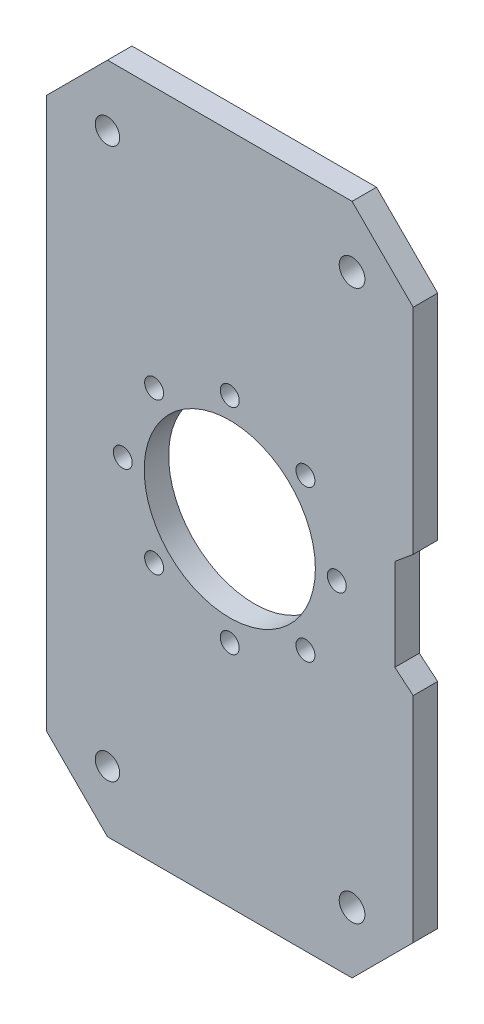
SolidWorks part; units mm, degrees
ref_plane "前视基准面" through (0, 0, 0) normal (0, 0, 1) x (1, 0, 0)
ref_plane "上视基准面" through (0, 0, 0) normal (0, 1, 0) x (1, 0, 0)
ref_plane "右视基准面" through (0, 0, 0) normal (1, 0, 0) x (0, 0, -1)
sketch "草图1" plane through (0, 0, 0) normal (0, 0, 1) x (1, 0, 0)
  line L1 (30, -55) -> (-30, -55)
  line L2 (30, -55) -> (30, 55)
  line L3 (30, 55) -> (-30, 55)
  line L4 (-30, -55) -> (-30, 55)
  line L5 (30, -55) -> (-30, 55) construction
  line L6 (30, 55) -> (-30, -55) construction
  line L7 (20, -45) -> (-20, -45) construction
  line L8 (20, -45) -> (20, 45) construction
  line L9 (20, 45) -> (-20, 45) construction
  line L10 (-20, -45) -> (-20, 45) construction
  line L11 (20, -45) -> (-20, 45) construction
  line L12 (20, 45) -> (-20, -45) construction
  circle A0 centre (0, 0) radius 14
  circle A1 centre (0, 0) radius 17.5 construction
  circle A4 centre (-20, 45) radius 2
  circle A5 centre (20, 45) radius 2.1
  circle A6 centre (-20, -45) radius 2
  circle A7 centre (20, -45) radius 2.1
  circle A8 centre (0, 17.5) radius 1.55
  circle A9 centre (12.3744, 12.3744) radius 1.55
  circle A10 centre (17.5, 0) radius 1.55
  circle A11 centre (12.3744, -12.3744) radius 1.55
  circle A12 centre (0, -17.5) radius 1.55
  circle A13 centre (-12.3744, -12.3744) radius 1.55
  circle A14 centre (-17.5, 0) radius 1.55
  circle A15 centre (-12.3744, 12.3744) radius 1.55
  point P34 (0, 0)
  dimension "D1" = 110
  dimension "D3" = 10
  dimension "D5" = 4
  dimension "D6" = 35
  dimension "D7" = 28
  dimension "D8" = 3.1
  dimension "D10" = 4.2
  dimension "D2" = 60
  dimension "D4" = 90
  dimension "D9" = 8
extrude "凸台-拉伸1" add sketch "草图1" along normal mid plane 4
chamfer "倒角1" distance 10 angle 45 4 edges at (-30, -55, 0) (30, -55, 0) (30, 55, 0) (-30, 55, 0)
sketch "草图2" plane through (0, 0, -2) normal (0, 0, -1) x (-1, 0, 0)
  line L0 (-30, -10) -> (-27, -7.5)
  line L1 (-30, -45) -> (-30, 45) construction
  line L2 (-27, -7.5) -> (-27, 7.5)
  line L3 (-27, 7.5) -> (-30, 10)
  line L4 (-30, 10) -> (-30, -10)
  point P8 (-30, 0)
  point P9 (-27, 0)
  dimension "D1" = 20
  dimension "D2" = 3
  dimension "D3" = 15
extrude "切除-拉伸1" cut sketch "草图2" against normal through all
